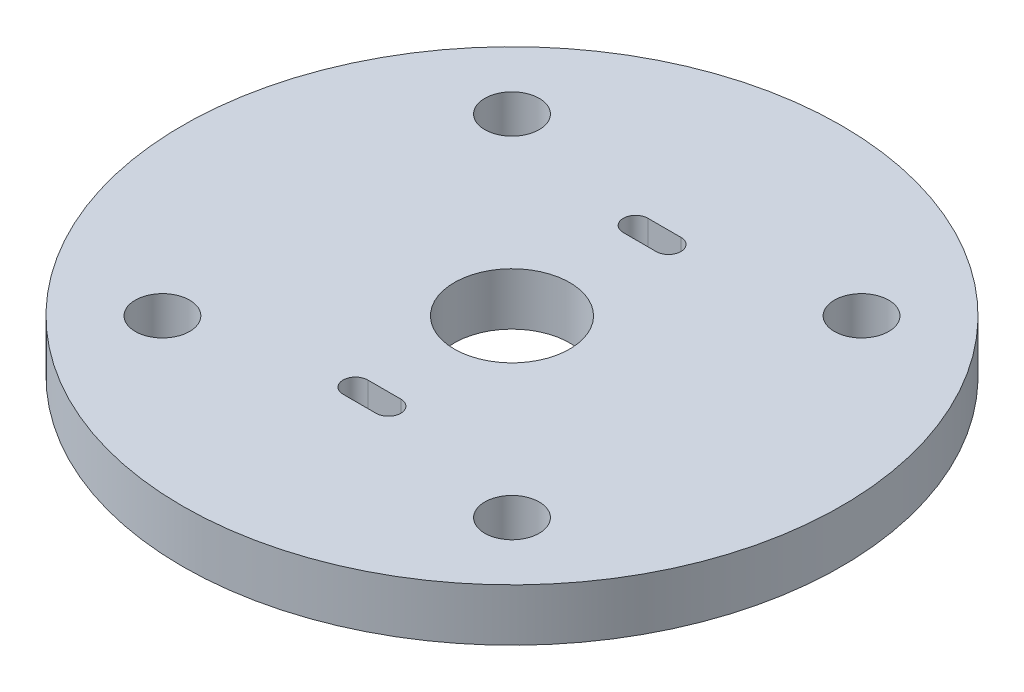
SolidWorks part; units mm, degrees
material "Acrylic (Medium-high impact)"
ref_plane "Front Plane" through (0, 0, 0) normal (0, 0, 1) x (1, 0, 0)
ref_plane "Top Plane" through (0, 0, 0) normal (0, 1, 0) x (1, 0, 0)
ref_plane "Right Plane" through (0, 0, 0) normal (1, 0, 0) x (0, 0, -1)
sketch "Sketch1" plane through (0, 0, 0) normal (0, 1, 0) x (1, 0, 0)
  line L0 (0, 10.6066) -> (21.2132, 10.6066) construction
  line L1 (0, 0) -> (21.2132, 0) construction
  line L2 (0, 0) -> (0, 21.2132) construction
  line L3 (0, 21.2132) -> (21.2132, 21.2132) construction
  line L4 (21.2132, 0) -> (21.2132, 21.2132) construction
  line L5 (10.6066, 10.6066) -> (10.6066, 16) construction
  line L10 (10.6066, 10.6066) -> (10.6066, 16) construction
  line L11 (0, 0) -> (21.2132, 21.2132) construction
  circle A0 centre (10.6066, 10.6066) radius 3.5
  circle A1 centre (0, 21.2132) radius 1.65
  circle A2 centre (21.2132, 21.2132) radius 1.65
  circle A3 centre (21.2132, 0) radius 1.65
  circle A4 centre (0, 0) radius 1.65
  circle A5 centre (10.6066, 10.6066) radius 20
  dimension "D1" = 7
  dimension "D2" = 3.3
  dimension "D4" = 40
  dimension "D3" = 30
extrude "Boss-Extrude1" add sketch "Sketch1" along normal blind 3.175
sketch "Sketch2" plane through (0, 3.175, 0) normal (0, 1, 0) x (1, 0, 0)
  line L0 (10.6066, 10.6066) -> (10.6066, 19.1066) construction
  line L1 (9.6066, 19.1066) -> (11.6066, 19.1066) construction
  line L2 (9.6066, 19.8566) -> (11.6066, 19.8566)
  line L3 (9.6066, 18.3566) -> (11.6066, 18.3566)
  line L4 (10.6066, 10.6066) -> (54, 10.6066) construction
  line L6 (9.6066, 2.1066) -> (11.6066, 2.1066) construction
  line L7 (9.6066, 1.3566) -> (11.6066, 1.3566)
  line L8 (9.6066, 2.8566) -> (11.6066, 2.8566)
  arc A0 (9.6066, 19.8566) -> (9.6066, 18.3566) centre (9.6066, 19.1066) ccw
  arc A1 (11.6066, 18.3566) -> (11.6066, 19.8566) centre (11.6066, 19.1066) ccw
  arc A2 (9.6066, 1.3566) -> (9.6066, 2.8566) centre (9.6066, 2.1066) cw
  arc A3 (11.6066, 2.8566) -> (11.6066, 1.3566) centre (11.6066, 2.1066) cw
  circle A4 centre (10.6066, 10.6066) radius 3.5 construction
  point P5 (10.6066, 19.1066)
  point P15 (10.6066, 2.1066)
  dimension "D1" = 1.5
  dimension "D2" = 2
  dimension "D3" = 8.5
extrude "Cut-Extrude1" cut sketch "Sketch2" against normal through all
